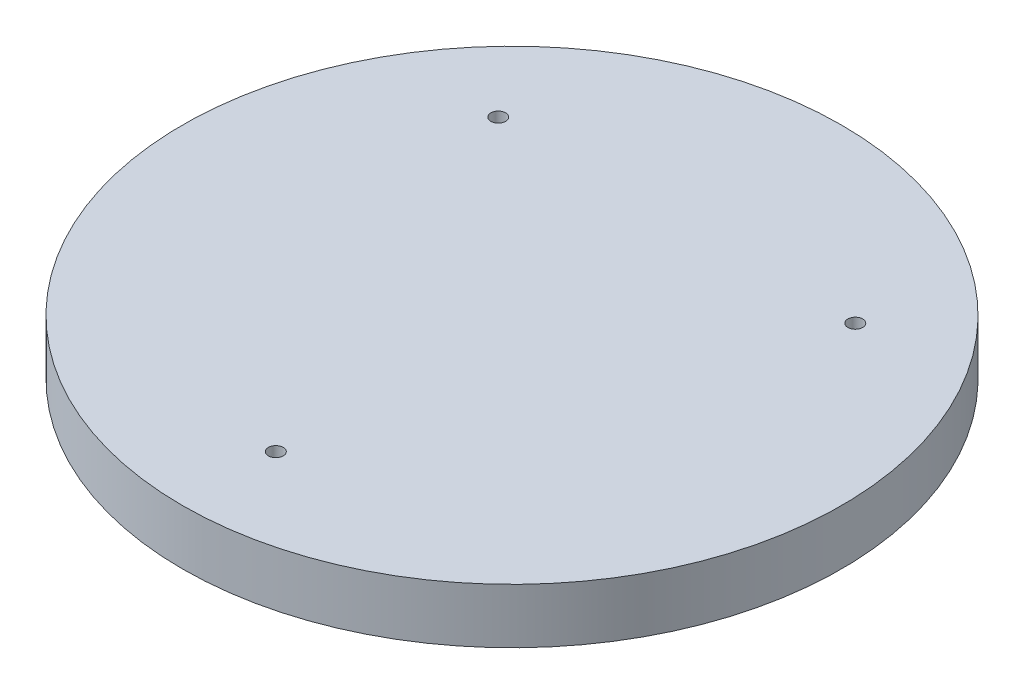
SolidWorks part; units mm, degrees
material "1060 Alloy"
ref_plane "Front Plane" through (0, 0, 0) normal (0, 0, 1) x (1, 0, 0)
ref_plane "Top Plane" through (0, 0, 0) normal (0, 1, 0) x (1, 0, 0)
ref_plane "Right Plane" through (0, 0, 0) normal (1, 0, 0) x (0, 0, -1)
sketch "Sketch1" plane through (0, 0, 0) normal (0, 1, 0) x (1, 0, 0)
  circle A0 centre (0, 0) radius 152.4
  dimension "D1" = 304.8
extrude "Boss-Extrude1" add sketch "Sketch1" along normal blind 25.4
sketch "Sketch2" plane through (0, 25.4, 0) normal (0, 1, 0) x (1, 0, 0)
  circle A0 centre (-82.55, 76.2) radius 3.429
  circle A1 centre (82.55, 76.2) radius 3.429
  circle A2 centre (0, -109.22) radius 3.429
  dimension "D1" = 6.858
  dimension "D2" = 6.858
  dimension "D3" = 6.858
  dimension "D9" = 82.55
  dimension "D8" = 185.42
  dimension "D4" = 165.1
  dimension "D5" = 82.55
  dimension "D6" = 185.42
  dimension "D7" = 76.2
extrude "Cut-Extrude1" cut sketch "Sketch2" against normal blind 12.7
